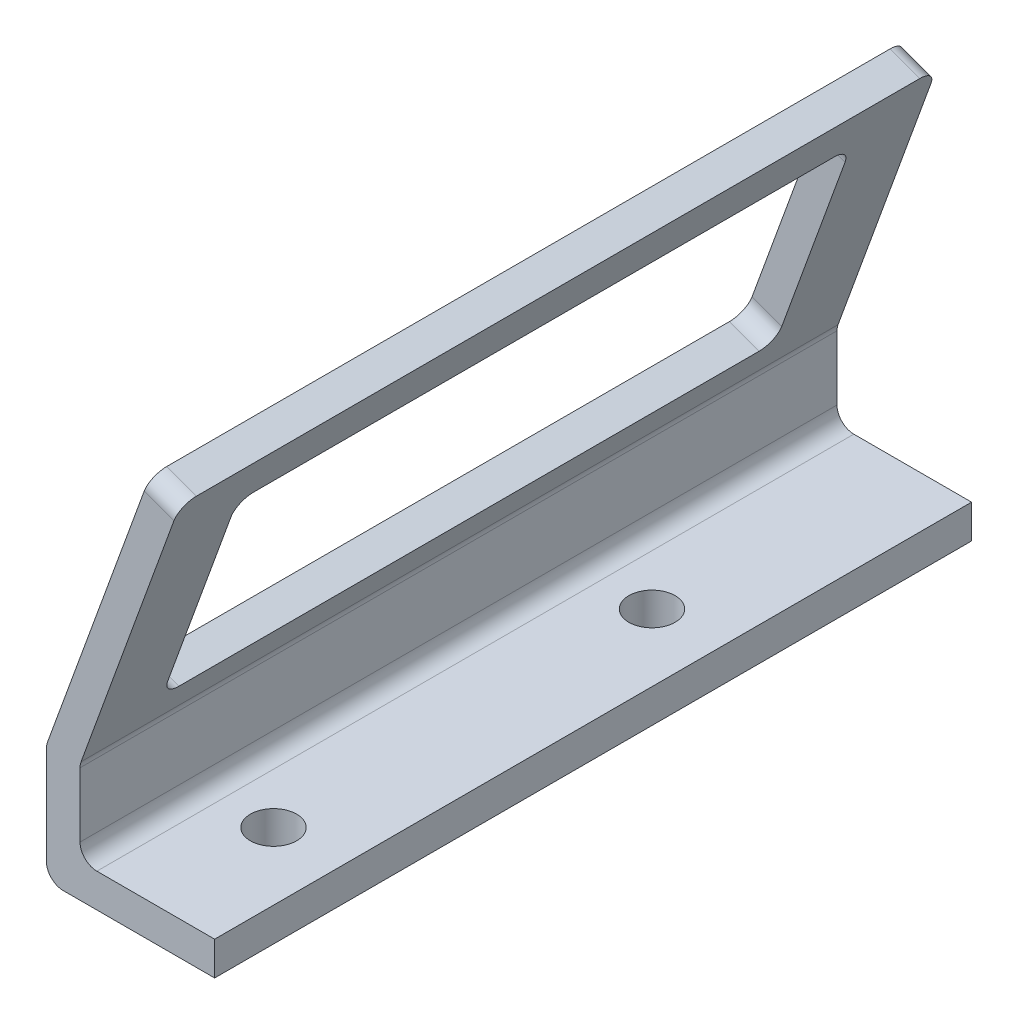
SolidWorks part; units mm, degrees
ref_plane "정면" through (0, 0, 0) normal (0, 0, 1) x (1, 0, 0)
ref_plane "윗면" through (0, 0, 0) normal (0, 1, 0) x (1, 0, 0)
ref_plane "우측면" through (0, 0, 0) normal (1, 0, 0) x (0, 0, -1)
sketch "스케치1" plane through (0, 0, 0) normal (0, 0, 1) x (1, 0, 0)
  line L0 (-10, 12) -> (2.3127, 45.8289)
  line L1 (-10, 2) -> (10, 2)
  line L2 (-10, 2) -> (-10, -2)
  line L3 (-10, -2) -> (10, -2)
  line L4 (10, 2) -> (10, -2)
  line L5 (-10, 2) -> (10, -2) construction
  line L6 (-10, -2) -> (10, 2) construction
  line L7 (-10, 2) -> (-6, 2)
  line L8 (-10, 2) -> (-10, 12)
  line L9 (-10, 12) -> (-6, 12)
  line L10 (-6, 2) -> (-6, 12)
  line L11 (2.3127, 45.8289) -> (5.8448, 44.5434)
  line L12 (5.8448, 44.5434) -> (-6, 12)
  point P0 (0, 0)
  dimension "D1" = 20
  dimension "D2" = 4
  dimension "D3" = 10
  dimension "D4" = 4
  dimension "D5" = 36
  dimension "D6" = 160
extrude "보스-돌출1" add sketch "스케치1" along normal mid plane 90 contours L12 L11 L0 L9 | L1 L10 L9 L8 | L4 L1 L2 L3
sketch "스케치2" plane through (-12.6869, 4.6177, 0) normal (-0.9397, 0.342, 0) x (0, 0, 1)
  line L0 (0, 43.8561) -> (0, 7.8561) construction
  line L1 (45, 43.8561) -> (-45, 43.8561) construction
  line L2 (45, 7.8561) -> (-45, 7.8561) construction
  line L3 (-45, 25.8561) -> (45, 25.8561) construction
  line L4 (-45, 7.8561) -> (-45, 43.8561) construction
  line L5 (45, 7.8561) -> (45, 43.8561) construction
  line L7 (-36.5, 38.8561) -> (36.5, 38.8561)
  line L8 (-36.5, 38.8561) -> (-36.5, 12.8561)
  line L9 (-36.5, 12.8561) -> (36.5, 12.8561)
  line L10 (36.5, 38.8561) -> (36.5, 12.8561)
  line L11 (-36.5, 38.8561) -> (36.5, 12.8561) construction
  line L12 (-36.5, 12.8561) -> (36.5, 38.8561) construction
  point P12 (0, 25.8561)
  dimension "D1" = 73
  dimension "D2" = 26
extrude "컷-돌출1" cut sketch "스케치2" against normal blind 5
fillet "필렛1" radius 2 10 edges at (-10, -2, 0) (-6, 2, 0) (-6, 12, 0) (-10, 12, 0) (4.0788, 45.1861, -45) (4.0788, 45.1861, 45) (2.3687, 40.4877, 36.5) (-6.5239, 16.0557, 36.5) (-6.5239, 16.0557, -36.5) (2.3687, 40.4877, -36.5)
sketch "스케치3" plane through (0, 2, 0) normal (0, 1, 0) x (1, 0, 0)
  line L0 (2, -45) -> (2, 45) construction
  line L1 (-4, -45) -> (10, -45) construction
  line L2 (-4, 45) -> (10, 45) construction
  line L3 (10, -45) -> (10, 45) construction
  circle A0 centre (2, -30) radius 2.75
  circle A1 centre (2, 15) radius 2.75
  dimension "D2" = 5.5
  dimension "D5" = 5.5
  dimension "D1" = 8
  dimension "D3" = 15
  dimension "D4" = 30
extrude "컷-돌출2" cut sketch "스케치3" against normal blind 5
